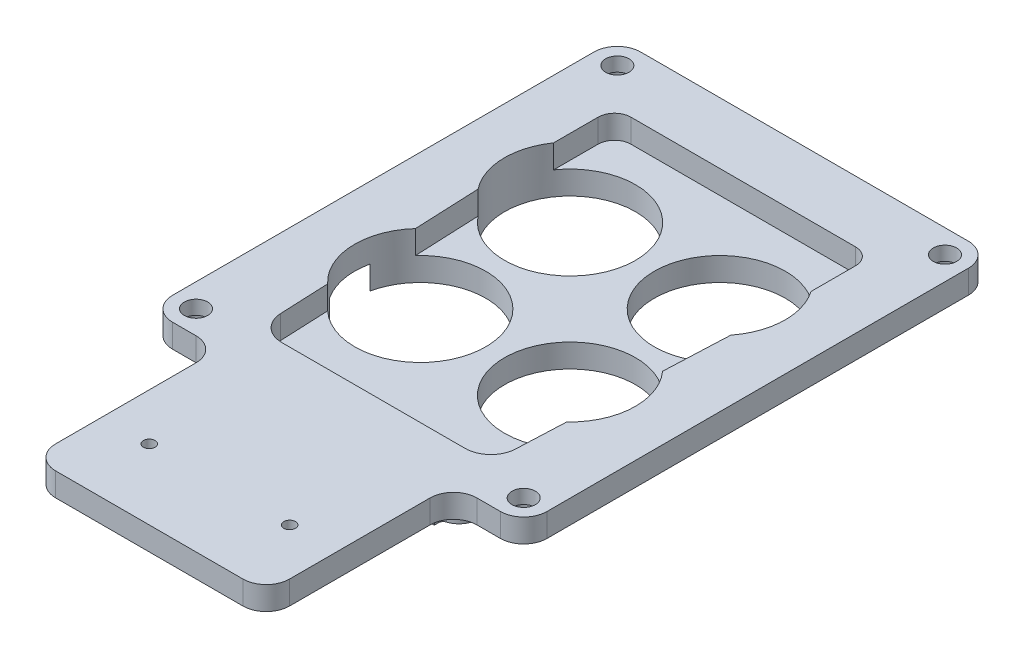
SolidWorks part; units mm, degrees
ref_plane "Front Plane" through (0, 0, 0) normal (0, 0, 1) x (1, 0, 0)
ref_plane "Top Plane" through (0, 0, 0) normal (0, 1, 0) x (1, 0, 0)
ref_plane "Right Plane" through (0, 0, 0) normal (1, 0, 0) x (0, 0, -1)
sketch "Sketch1" plane through (0, 0, 0) normal (0, 1, 0) x (1, 0, 0)
  line L0 (-32, 36) -> (-32, 21)
  line L3 (-24, 44) -> (24, 44)
  line L7 (32, 36) -> (32, 21)
  line L8 (-32, 21) -> (-29.5796, -34.4362)
  line L9 (-19.5891, -44) -> (19.5891, -44)
  line L10 (29.5796, -34.4362) -> (32, 21)
  line L11 (-24, 41) -> (24, 41)
  line L12 (29, 36) -> (29, 21.0655)
  line L13 (26.5825, -34.3053) -> (29, 21.0655)
  line L14 (-19.5891, -41) -> (19.5891, -41)
  line L15 (-29, 21.0655) -> (-26.5825, -34.3053)
  line L16 (-29, 36) -> (-29, 21.0655)
  line L17 (-35, -47.4) -> (35, -47.4)
  line L18 (-40, -42.4) -> (-40, 47.6)
  line L19 (-35, 52.6) -> (35, 52.6)
  line L20 (40, -42.4) -> (40, 47.6)
  line L21 (-24, 39.5) -> (24, 39.5)
  line L22 (27.5, 36) -> (27.5, 21.0982)
  line L23 (25.0839, -34.2399) -> (27.5, 21.0982)
  line L24 (-19.5891, -39.5) -> (19.5891, -39.5)
  line L25 (-27.5, 21.0982) -> (-25.0839, -34.2399)
  line L26 (-27.5, 36) -> (-27.5, 21.0982)
  arc A2 (-19.5891, -44) -> (-29.5796, -34.4362) centre (-19.5891, -34) cw
  arc A3 (29.5796, -34.4362) -> (19.5891, -44) centre (19.5891, -34) cw
  arc A4 (-24, 44) -> (-32, 36) centre (-24, 36) ccw
  arc A5 (32, 36) -> (24, 44) centre (24, 36) ccw
  arc A6 (29, 36) -> (24, 41) centre (24, 36) ccw
  arc A7 (26.5825, -34.3053) -> (19.5891, -41) centre (19.5891, -34) cw
  arc A8 (-19.5891, -41) -> (-26.5825, -34.3053) centre (-19.5891, -34) cw
  arc A9 (-24, 41) -> (-29, 36) centre (-24, 36) ccw
  arc A10 (-40, -42.4) -> (-35, -47.4) centre (-35, -42.4) ccw
  arc A11 (35, -47.4) -> (40, -42.4) centre (35, -42.4) ccw
  arc A12 (40, 47.6) -> (35, 52.6) centre (35, 47.6) ccw
  arc A13 (-35, 52.6) -> (-40, 47.6) centre (-35, 47.6) ccw
  arc A14 (27.5, 36) -> (24, 39.5) centre (24, 36) ccw
  arc A15 (25.0839, -34.2399) -> (19.5891, -39.5) centre (19.5891, -34) cw
  arc A16 (-19.5891, -39.5) -> (-25.0839, -34.2399) centre (-19.5891, -34) cw
  arc A17 (-24, 39.5) -> (-27.5, 36) centre (-24, 36) ccw
  point P0 (0, 0)
  point P32 (0, 4.1)
  dimension "D1" = 177.5
  dimension "D4" = 8
  dimension "D5" = 8
  dimension "D8" = 15
  dimension "D13" = 10
  dimension "D14" = 10
  dimension "D12" = 5
  dimension "D2" = 44
  dimension "D3" = 177.5
  dimension "D6" = 32
  dimension "D7" = 32
  dimension "D9" = 15
  dimension "D10" = 44
  dimension "D11" = 3
  dimension "D15" = 100
  dimension "D16" = 80
  dimension "D17" = 48.5
  dimension "D18" = 40
  dimension "D19" = 4.1
  dimension "D20" = 1.5
ref_plane "Plane1" through (0, 25, 0) normal (0, 1, 0) x (1, 0, 0)
sketch "Sketch8" plane through (0, 0, 0) normal (0, 1, 0) x (-1, 0, 0)
  line L0 (32.15, -40) -> (32.15, -19)
  line L1 (28.15, -44) -> (-28.15, -44)
  line L2 (-32.15, -40) -> (-32.15, -19)
  line L3 (32.15, -19) -> (31.2331, 2)
  line L5 (-31.2331, 2) -> (-32.15, -19)
  line L7 (16, 13.5) -> (-16, -18.5) construction
  line L8 (20.5, 47) -> (20.5, 46.0775)
  line L9 (-16, 13.5) -> (16, -18.5) construction
  line L12 (20.5, 47) -> (-20.5, 47) construction
  line L13 (21.5547, 45) -> (-21.5547, 45) construction
  line L14 (31.2331, 2) -> (-31.2331, 2) construction
  line L15 (24, 42) -> (-24, 42) construction
  line L16 (-31.2331, 2) -> (-24, 42)
  line L17 (24, 42) -> (31.2331, 2)
  line L18 (-20.5, 47) -> (-20.5, 46.0775)
  arc A2 (28.15, -44) -> (32.15, -40) centre (28.15, -40) ccw
  arc A3 (-32.15, -40) -> (-28.15, -44) centre (-28.15, -40) ccw
  circle A4 centre (16, 13.5) radius 12.5
  circle A8 centre (-16, 13.5) radius 12.5
  circle A9 centre (16, -18.5) radius 12.5
  circle A10 centre (-16, -18.5) radius 12.5
  arc A13 (20.5, 47) -> (-20.5, 47) centre (0, -162.625) ccw
  arc A14 (20.5, 46.0775) -> (21.2128, 45.1197) centre (21.5, 46.0775) ccw
  arc A15 (24, 42) -> (21.2128, 45.1197) centre (20.0638, 41.2882) ccw
  arc A18 (-24, 42) -> (-21.2128, 45.1197) centre (-20.0638, 41.2882) cw
  arc A19 (-20.5, 46.0775) -> (-21.2128, 45.1197) centre (-21.5, 46.0775) cw
  point P0 (0, 0)
  point P29 (0, 48)
  point P38 (0, 2)
  point P44 (0, 47)
  point P45 (0, 42)
  dimension "D7" = 1
  dimension "D8" = 3
  dimension "D9" = 4
  dimension "D10" = 4
  dimension "D13" = 25
  dimension "D14" = 25.5
  dimension "D20" = 25
  dimension "D21" = 25
  dimension "D22" = 25
  dimension "D28" = 2
  dimension "D32" = 8
  dimension "D33" = 2
  dimension "D6" = 4
  dimension "D23" = 3
  dimension "D1" = 44
  dimension "D2" = 177.5
  dimension "D3" = 177.5
  dimension "D4" = 32.15
  dimension "D5" = 32.15
  dimension "D11" = 25
  dimension "D12" = 21
  dimension "D15" = 32
  dimension "D16" = 32
  dimension "D17" = 32
  dimension "D18" = 32
  dimension "D19" = 16
  dimension "D24" = 3.1197
  dimension "D25" = 0.9225
  dimension "D29" = 46
  dimension "D30" = 40
  dimension "D31" = 48
extrude "Boss-Extrude6" add sketch "Sketch8" against normal blind 5 separate body
extrude "Boss-Extrude7" add sketch "Sketch1" along normal blind 5 contours L19 A13 L18 A10 L17 A11 L20 A12 A5 L7 L10 A3 L9 A2 L8 L0 A4 L3 | L7 A5 L3 A4 L0 L8 A2 L9 A3 L10 A9 L11 A6 L12 L13 A7 L14 A8 L15 L16 | L11 A9 L16 L15 A8 L14 A7 L13 L12 A6 A17 L21 A14 L22 L23 A15 L24 A16 L25 L26
ref_plane "Plane2" through (0, 38, 0) normal (0, 1, 0) x (1, 0, 0)
sketch "Sketch2" plane through (0, 25, 0) normal (0, 1, 0) x (1, 0, 0)
  line L1 (-35, -45.9) -> (35, -45.9)
  line L2 (-40, -40.9) -> (-40, 49.1)
  line L3 (-35, 54.1) -> (35, 54.1)
  line L4 (40, -40.9) -> (40, 49.1)
  arc A0 (-40, -40.9) -> (-35, -45.9) centre (-35, -40.9) ccw
  arc A1 (35, -45.9) -> (40, -40.9) centre (35, -40.9) ccw
  arc A2 (40, 49.1) -> (35, 54.1) centre (35, 49.1) ccw
  arc A3 (-35, 54.1) -> (-40, 49.1) centre (-35, 49.1) ccw
  point P0 (0, 4.1)
  dimension "D3" = 5
  dimension "D1" = 100
  dimension "D2" = 80
  dimension "D4" = 50
  dimension "D5" = 40
  dimension "D6" = 4.1
extrude "Extrude-Thin4" add sketch "Sketch2" against normal up to surface (20 mm away) and the other way blind 8 separate body thin contours L3 A2 L4 A1 L1 A0 L2 A3
sketch "Sketch10" plane through (0, 38, 0) normal (0, 1, 0) x (1, 0, 0)
  line L0 (-32, 36) -> (-32, 21)
  line L1 (-24, 44) -> (24, 44)
  line L2 (32, 36) -> (32, 21)
  line L3 (-32, 21) -> (-29.5796, -34.4362)
  line L4 (-19.5891, -44) -> (19.5891, -44)
  line L5 (29.5796, -34.4362) -> (32, 21)
  arc A0 (-19.5891, -44) -> (-29.5796, -34.4362) centre (-19.5891, -34) cw
  arc A1 (29.5796, -34.4362) -> (19.5891, -44) centre (19.5891, -34) cw
  arc A2 (-24, 44) -> (-32, 36) centre (-24, 36) ccw
  arc A3 (32, 36) -> (24, 44) centre (24, 36) ccw
  point P0 (0, 0)
  dimension "D7" = 10
  dimension "D8" = 10
  dimension "D9" = 8
  dimension "D10" = 8
  dimension "D1" = 44
  dimension "D2" = 177.5
  dimension "D3" = 177.5
  dimension "D4" = 32
  dimension "D5" = 32
  dimension "D6" = 44
  dimension "D11" = 15
  dimension "D12" = 15
extrude "Boss-Extrude8" add sketch "Sketch10" along normal blind 5 separate body
sketch "Sketch11" plane through (0, 38, 0) normal (0, 1, 0) x (1, 0, 0)
  line L0 (-35, -45.9) -> (35, -45.9)
  line L1 (-40, -40.9) -> (-40, 49.1)
  line L2 (-35, 54.1) -> (35, 54.1)
  line L3 (40, -40.9) -> (40, 49.1)
  line L4 (-35, 54.1) -> (35, 54.1) construction
  line L5 (40, -40.9) -> (40, 49.1) construction
  line L6 (-35, -45.9) -> (35, -45.9) construction
  arc A0 (-40, -40.9) -> (-35, -45.9) centre (-35, -40.9) ccw
  arc A1 (35, -45.9) -> (40, -40.9) centre (35, -40.9) ccw
  arc A2 (40, 49.1) -> (35, 54.1) centre (35, 49.1) ccw
  arc A3 (-35, 54.1) -> (-40, 49.1) centre (-35, 49.1) ccw
  dimension "D1" = 5
extrude "Boss-Extrude9" add sketch "Sketch11" against normal blind 5
sketch "Sketch13" plane through (0, 0, 0) normal (1, 0, 0) x (0, 0, -1)
  line L1 (49.1, 11.1) -> (42.6, 11.1)
  line L2 (49.1, 11.1) -> (49.1, 28.9)
  line L3 (49.1, 28.9) -> (42.6, 28.9)
  line L4 (42.6, 11.1) -> (42.6, 28.9)
  line L5 (-34.4, 11.1) -> (-40.9, 11.1)
  line L6 (-34.4, 11.1) -> (-34.4, 28.9)
  line L7 (-34.4, 28.9) -> (-40.9, 28.9)
  line L8 (-40.9, 11.1) -> (-40.9, 28.9)
  line L9 (-40.9, 33) -> (-40.9, 5) construction
  line L10 (49.1, 33) -> (49.1, 5) construction
  dimension "D1" = 17.8
  dimension "D2" = 6.5
  dimension "D3" = 11.1
  dimension "D4" = 17.8
  dimension "D5" = 6.5
  dimension "D6" = 11.1
extrude "Boss-Extrude10" add sketch "Sketch13" along normal through all and the other way through all
sketch "Sketch15" plane through (0, 11.1, 0) normal (0, -1, 0) x (1, 0, 0)
  line L0 (35, -49.1) -> (-35, -49.1) construction
  line L1 (-35, -42.6) -> (-35, -49.1) construction
  line L3 (-35, 40.9) -> (-35, 34.4) construction
  line L4 (-35, 40.9) -> (35, 40.9) construction
  line L6 (0, -55) -> (0, 55) construction
  circle A0 centre (-21.9, -44) radius 2.25
  circle A1 centre (-9.9, -44) radius 2.25
  circle A2 centre (-21.9, 35.8) radius 2.25
  circle A3 centre (-9.9, 35.8) radius 2.25
  circle A4 centre (9.9, 35.8) radius 2.25
  circle A5 centre (21.9, 35.8) radius 2.25
  circle A6 centre (9.9, -44) radius 2.25
  circle A7 centre (21.9, -44) radius 2.25
  dimension "D1" = 5.1
  dimension "D2" = 4.5
  dimension "D5" = 4.5
  dimension "D6" = 4.5
  dimension "D8" = 4.5
  dimension "D3" = 13.1
  dimension "D4" = 12
  dimension "D7" = 12
  dimension "D9" = 5.1
  dimension "D10" = 13.1
extrude "Cut-Extrude1" cut sketch "Sketch15" against normal up to surface (17.8 mm away) contours A5
sketch "Sketch17" plane through (0, -5, 0) normal (0, 1, 0) x (1, 0, 0)
  line L0 (0, 0) -> (0, 52.6) construction
  line L5 (18, 46.5) -> (18, 43.5)
  line L6 (18, 46.5) -> (-18, 46.5)
  line L7 (18, 43.5) -> (-18, 43.5)
  line L8 (-18, 46.5) -> (-18, 43.5)
  line L9 (18, 46.5) -> (-18, 43.5) construction
  line L10 (18, 43.5) -> (-18, 46.5) construction
  line L11 (-35, 52.6) -> (35, 52.6) construction
  line L16 (-12.5, -47.1279) -> (-12.5, -50.1331)
  line L17 (-12.5, -50.1331) -> (12.5, -50.1331) construction
  line L18 (12.5, -50.1331) -> (12.5, -47.1279)
  line L19 (-31.5, 21.0109) -> (-30.8457, 6.0252)
  line L21 (-30.8457, 6.0252) -> (-33.8429, 5.8943)
  line L22 (-33.8429, 5.8943) -> (-34.5, 20.9454)
  line L24 (-34.5, 31.0109) -> (-34.5, 20.9454)
  line L25 (-31.5, 31.0109) -> (-34.5, 31.0109)
  line L27 (28.15, 44) -> (-28.15, 44) construction
  line L31 (29.0801, -34.4144) -> (31.5, 21.0109) construction
  line L32 (31.5, 21.0109) -> (31.5, 31.0109) construction
  line L33 (-31.5, 21.0109) -> (-31.5, 31.0109)
  line L40 (31.5, 21.0109) -> (31.5, 31.0109)
  line L41 (31.5, 31.0109) -> (34.5, 31.0109)
  line L46 (34.5, 31.0109) -> (34.5, 20.9454)
  line L47 (31.5, 21.0109) -> (30.8457, 6.0252)
  line L48 (30.8457, 6.0252) -> (33.8429, 5.8943)
  line L49 (33.8429, 5.8943) -> (34.5, 20.9454)
  arc A2 (-20.7433, -49.4881) -> (20.7433, -49.4881) centre (0, 162.625) ccw
  arc A3 (-12.5, -50.1331) -> (12.5, -50.1331) centre (0, 162.625) ccw
  arc A5 (-20.4513, -46.5024) -> (20.4513, -46.5024) centre (0, 162.625) ccw
  arc A6 (-12.5, -47.1279) -> (12.5, -47.1279) centre (0, 162.625) ccw
  point P1 (0, 45)
  dimension "D1" = 36
  dimension "D2" = 3
  dimension "D3" = 2.5
  dimension "D4" = 0.5
  dimension "D5" = 0.5
  dimension "D6" = 25
  dimension "D7" = 3
  dimension "D8" = 3
  dimension "D12" = 10
  dimension "D13" = 15
sketch "Sketch18" plane through (0, 43, 0) normal (0, 1, 0) x (1, 0, 0)
  line L5 (18, 46.5) -> (18, 43.5)
  line L6 (18, 46.5) -> (-18, 46.5)
  line L7 (18, 43.5) -> (-18, 43.5)
  line L8 (-18, 46.5) -> (-18, 43.5)
  line L9 (18, 46.5) -> (-18, 43.5) construction
  line L10 (18, 43.5) -> (-18, 46.5) construction
  line L12 (-13, -46.5) -> (13, -46.5)
  line L13 (-13, -46.5) -> (-13, -43.5)
  line L14 (-13, -43.5) -> (13, -43.5)
  line L15 (13, -46.5) -> (13, -43.5)
  line L16 (-13, -46.5) -> (13, -43.5) construction
  line L17 (-13, -43.5) -> (13, -46.5) construction
  line L19 (-31.5, 21.0109) -> (-30.8457, 6.0252)
  line L21 (-30.8457, 6.0252) -> (-33.8429, 5.8943)
  line L22 (-33.8429, 5.8943) -> (-34.5, 20.9454)
  line L24 (-34.5, 31.0109) -> (-34.5, 20.9454)
  line L25 (-31.5, 31.0109) -> (-34.5, 31.0109)
  line L31 (29.0801, -34.4144) -> (31.5, 21.0109) construction
  line L32 (31.5, 21.0109) -> (31.5, 31.0109) construction
  line L33 (-31.5, 21.0109) -> (-31.5, 31.0109)
  line L40 (31.5, 21.0109) -> (31.5, 31.0109)
  line L41 (31.5, 31.0109) -> (34.5, 31.0109)
  line L46 (34.5, 31.0109) -> (34.5, 20.9454)
  line L47 (31.5, 21.0109) -> (30.8457, 6.0252)
  line L48 (30.8457, 6.0252) -> (33.8429, 5.8943)
  line L49 (33.8429, 5.8943) -> (34.5, 20.9454)
  point P1 (0, 45)
  point P3 (0, -45)
  dimension "D1" = 36
  dimension "D2" = 3
  dimension "D3" = 3
  dimension "D4" = 26
  dimension "D7" = 3
  dimension "D8" = 3
  dimension "D12" = 10
  dimension "D13" = 15
extrude "Boss-Extrude11" add sketch "Sketch17" along normal blind 2
extrude "Boss-Extrude12" add sketch "Sketch18" against normal blind 2
ref_plane "Plane6" through (0, 5, 0) normal (0, 1, 0) x (1, 0, 0)
sketch "Sketch19" plane through (0, 5, 0) normal (0, 1, 0) x (1, 0, 0)
  line L1 (75, -75) -> (-75, -75)
  line L2 (75, -75) -> (75, 75)
  line L3 (75, 75) -> (-75, 75)
  line L4 (-75, -75) -> (-75, 75)
  line L5 (75, -75) -> (-75, 75) construction
  line L6 (75, 75) -> (-75, -75) construction
  point P0 (0, 0)
extrude "Cut-Extrude2" cut sketch "Sketch19" along normal through all
sketch "Sketch20" plane through (0, 5, 0) normal (0, 1, 0) x (1, 0, 0)
  circle A0 centre (-35, 47.6) radius 2.5
  circle A1 centre (35, 47.6) radius 2.5
  circle A2 centre (-35, -42.4) radius 2.5
  circle A3 centre (35, -42.4) radius 2.5
  arc A4 (-35, 52.6) -> (-40, 47.6) centre (-35, 47.6) ccw construction
  arc A6 (40, 47.6) -> (35, 52.6) centre (35, 47.6) ccw construction
  arc A7 (-40, -42.4) -> (-35, -47.4) centre (-35, -42.4) ccw construction
  arc A8 (35, -47.4) -> (40, -42.4) centre (35, -42.4) ccw construction
  dimension "D1" = 5
  dimension "D2" = 5
  dimension "D3" = 5
  dimension "D4" = 5
extrude "Cut-Extrude3" cut sketch "Sketch20" against normal through all
sketch "Sketch21" plane through (0, -5, 0) normal (0, -1, 0) x (1, 0, 0)
  line L0 (0, 0) -> (0, 46.5) construction
  line L5 (-13.05, 35.5) -> (-8.15, 35.5)
  line L6 (-13.05, 35.5) -> (-13.05, 28.9)
  line L7 (-13.05, 28.9) -> (-8.15, 28.9)
  line L8 (-8.15, 35.5) -> (-8.15, 28.9)
  line L10 (8.15, 35.5) -> (8.15, 28.9)
  line L11 (13.05, 28.9) -> (8.15, 28.9)
  line L12 (13.05, 35.5) -> (13.05, 28.9)
  line L13 (13.05, 35.5) -> (8.15, 35.5)
  circle A0 centre (-16, 13.5) radius 12.5 construction
  dimension "D1" = 6.6
  dimension "D2" = 4.9
  dimension "D3" = 8.15
  dimension "D4" = 15.4
extrude "Boss-Extrude13" add sketch "Sketch21" along normal blind 5
sketch "Sketch22" plane through (0, 5, 0) normal (0, 1, 0) x (1, 0, 0)
  line L0 (-35, -47.4) -> (-15.8868, -47.4) construction
  line L1 (25, -87.4) -> (-25, -87.4)
  line L2 (25, -87.4) -> (25, -47.4)
  line L3 (25, -47.4) -> (-25, -47.4)
  line L4 (-25, -87.4) -> (-25, -47.4)
  line L5 (25, -87.4) -> (-25, -47.4) construction
  line L6 (25, -47.4) -> (-25, -87.4) construction
  line L7 (0, -5.5) -> (0, 5.5) construction
  circle A0 centre (15, -72.4) radius 1.25
  circle A1 centre (-15, -72.4) radius 1.25
  point P0 (0, -67.4)
  dimension "D3" = 5
  dimension "D4" = 2.5
  dimension "D1" = 40
  dimension "D2" = 50
  dimension "D5" = 15
extrude "Boss-Extrude14" add sketch "Sketch22" against normal blind 5 contours L4 L1 L2 L3 A0 A1
fillet "Fillet1" radius 5 4 edges at (-25, 2.5, 47.4) (-25, 2.5, 87.4) (25, 2.5, 87.4) (25, 2.5, 47.4)
sketch "Sketch24" plane through (0, 0, 0) normal (0, -1, 0) x (1, 0, 0)
  circle A0 centre (35, -47.6) radius 3.75
  circle A1 centre (-35, -47.6) radius 3.75
  circle A2 centre (35, 42.4) radius 3.75
  circle A3 centre (-35, 42.4) radius 3.75
  dimension "D1" = 7.5
  dimension "D2" = 7.5
  dimension "D3" = 7.5
  dimension "D4" = 7.5
extrude "Cut-Extrude4" cut sketch "Sketch24" against normal blind 2
fillet "Fillet3" radius 1 16 edges at (-10.6, -10, 35.5) (-8.15, -10, 32.2) (-10.6, -10, 28.9) (-13.05, -10, 32.2) (13.05, -10, 32.2) (10.6, -10, 28.9) (8.15, -10, 32.2) (10.6, -10, 35.5) (-13.05, -7.5, 35.5) (-8.15, -7.5, 35.5) (8.15, -7.5, 35.5) (13.05, -7.5, 35.5) (13.05, -7.5, 28.9) (8.15, -7.5, 28.9) (-8.15, -7.5, 28.9) (-13.05, -7.5, 28.9)
sketch "Sketch25" plane through (0, -5, 0) normal (0, -1, 0) x (1, 0, 0)
  line L0 (28.15, -44) -> (18, -44) construction
  line L1 (16.5, -39) -> (-16.5, -39)
  line L2 (16.5, -39) -> (16.5, -43)
  line L3 (16.5, -43) -> (-16.5, -43)
  line L4 (-16.5, -39) -> (-16.5, -43)
  line L5 (16.5, -39) -> (-16.5, -43) construction
  line L6 (16.5, -43) -> (-16.5, -39) construction
  point P0 (0, -41)
  dimension "D1" = 1
  dimension "D2" = 33
  dimension "D3" = 4
  dimension "D4" = 0
extrude "Cut-Extrude5" cut sketch "Sketch25" against normal blind 2.5
sketch "Sketch26" plane through (0, -5, 0) normal (0, -1, 0) x (1, 0, 0)
  circle A0 centre (16, -18.5) radius 14
  circle A1 centre (16, 13.5) radius 14
  circle A2 centre (-16, 13.5) radius 14
  circle A3 centre (-16, -18.5) radius 14
  dimension "D1" = 28
  dimension "D2" = 28
  dimension "D3" = 28
  dimension "D4" = 28
extrude "Cut-Extrude6" cut sketch "Sketch26" against normal through all
equation "\"2.5.00mm\"=10"
